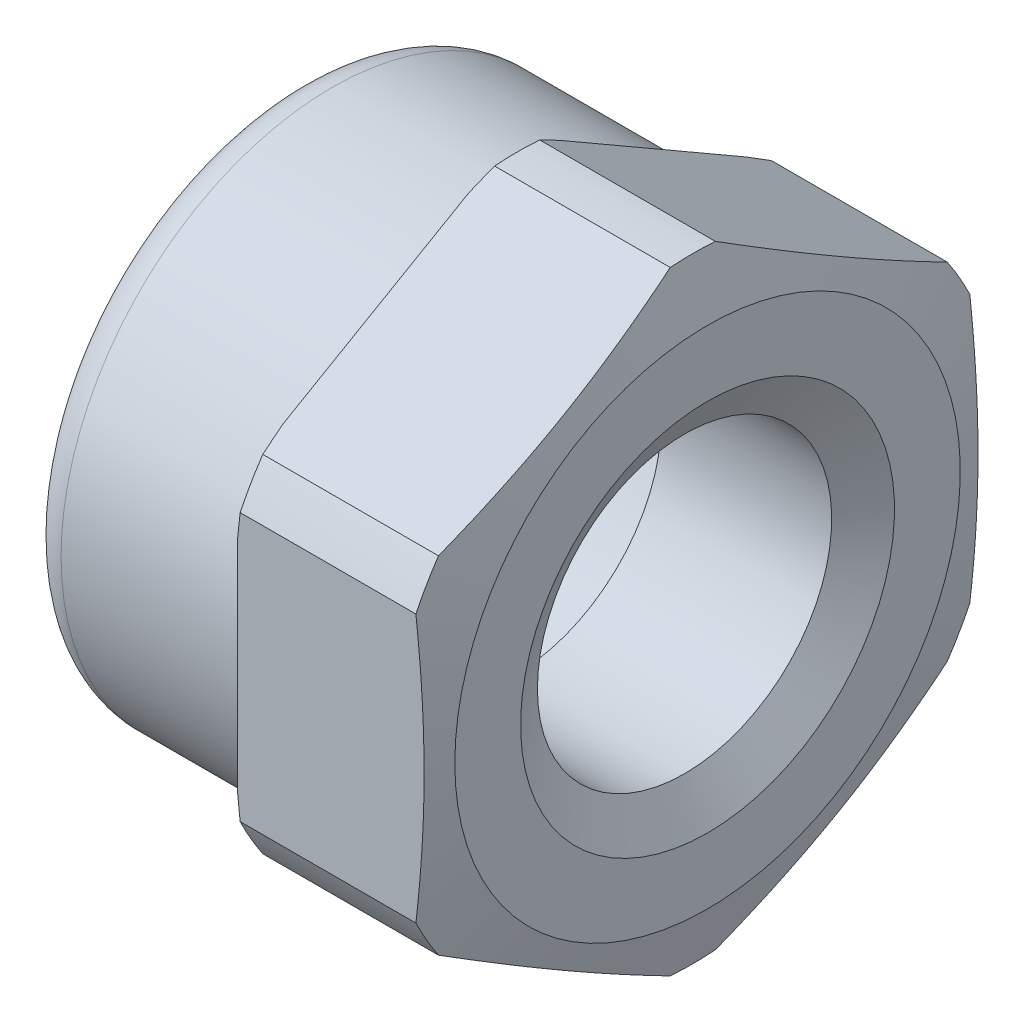
SolidWorks part; units mm, degrees
material "AISI 1020"
ref_plane "Спереди" through (0, 0, 0) normal (0, 0, 1) x (1, 0, 0)
ref_plane "Сверху" through (0, 0, 0) normal (0, 1, 0) x (1, 0, 0)
ref_plane "Справа" through (0, 0, 0) normal (1, 0, 0) x (0, 0, -1)
sketch "Эскиз1" plane through (0, 0, 0) normal (0, 0, 1) x (1, 0, 0)
  line L0 (-11.9, 6.7736) -> (-11.9, 5) construction
  line L2 (-5.5, 8.885) -> (-5.5827, 8.5764) construction
  line L3 (-0.4247, 8.885) -> (-5.5, 8.885) construction
  line L4 (0, 7.3) -> (-0.4247, 8.885) construction
  line L5 (0, 4.25) -> (0, 7.3) construction
  line L6 (0, 4.25) -> (-5.5827, 4.25) construction
  line L7 (-5.5827, 4.25) -> (-5.5827, 6.7736) construction
  line L8 (-10.8471, 6.7736) -> (-5.5827, 6.7736) construction
  line L9 (-10.8471, 5) -> (-10.8471, 6.7736) construction
  line L10 (-11.9, 5) -> (-10.8471, 5) construction
  line L11 (-11.9, 6.7736) -> (-11.9, 5)
  line L13 (-5.5, 8.885) -> (-5.5827, 8.5764)
  line L14 (-0.4247, 8.885) -> (-5.5, 8.885)
  line L15 (0, 7.3) -> (-0.4247, 8.885)
  line L16 (0, 4.25) -> (0, 7.3)
  line L17 (0, 4.25) -> (-5.5827, 4.25)
  line L18 (-5.5827, 4.25) -> (-5.5827, 6.7736)
  line L19 (-10.8471, 6.7736) -> (-5.5827, 6.7736)
  line L20 (-10.8471, 5) -> (-10.8471, 6.7736)
  line L21 (-11.9, 5) -> (-10.8471, 5)
  line L22 (-1000, 0) -> (49000, 0) construction
  line L24 (-5.5827, 7.8264) -> (-10.8471, 7.8264) construction
  line L25 (-5.5827, 7.8264) -> (-10.8471, 7.8264)
  line L26 (-5.5827, 8.5764) -> (-5.5827, 7.8264) construction
  line L27 (-5.5827, 8.5764) -> (-5.5827, 7.8264)
  arc A0 (-10.8471, 7.8264) -> (-11.9, 6.7736) centre (-10.8471, 6.7736) ccw construction
  arc A1 (-10.8471, 7.8264) -> (-11.9, 6.7736) centre (-10.8471, 6.7736) ccw
revolve "Повернуть1" add sketch "Эскиз1" angle 360 about L22
sketch "Эскиз2" plane through (0, 0, 0) normal (1, 0, 0) x (0, 0, -1)
  line L0 (8, -4.6188) -> (8, 4.6188) construction
  line L1 (0, -9.2376) -> (8, -4.6188) construction
  line L2 (-8, -4.6188) -> (0, -9.2376) construction
  line L3 (-8, 4.6188) -> (-8, -4.6188) construction
  line L4 (0, 9.2376) -> (-8, 4.6188) construction
  line L5 (8, 4.6188) -> (0, 9.2376) construction
  line L6 (8, -4.6188) -> (8, 4.6188)
  line L7 (0, -9.2376) -> (8, -4.6188)
  line L8 (-8, -4.6188) -> (0, -9.2376)
  line L9 (-8, 4.6188) -> (-8, -4.6188)
  line L10 (0, 9.2376) -> (-8, 4.6188)
  line L11 (8, 4.6188) -> (0, 9.2376)
extrude "Вырез-Вытянуть1" cut sketch "Эскиз2" against normal through all flip side to cut
sketch "Эскиз3" plane through (0, 0, 0) normal (0, 0, 1) x (1, 0, 0)
  line L0 (0, 0) -> (0, 5.4)
  line L1 (0, 5.4) -> (-0.664, 4.25)
  line L2 (-0.664, 4.25) -> (-0.664, 0)
  line L3 (-201000, 0) -> (249000, 0) construction
  line L4 (-0.664, 0) -> (0, 0)
revolve "Вырез-Повернуть1" cut sketch "Эскиз3" angle 360 about L4
